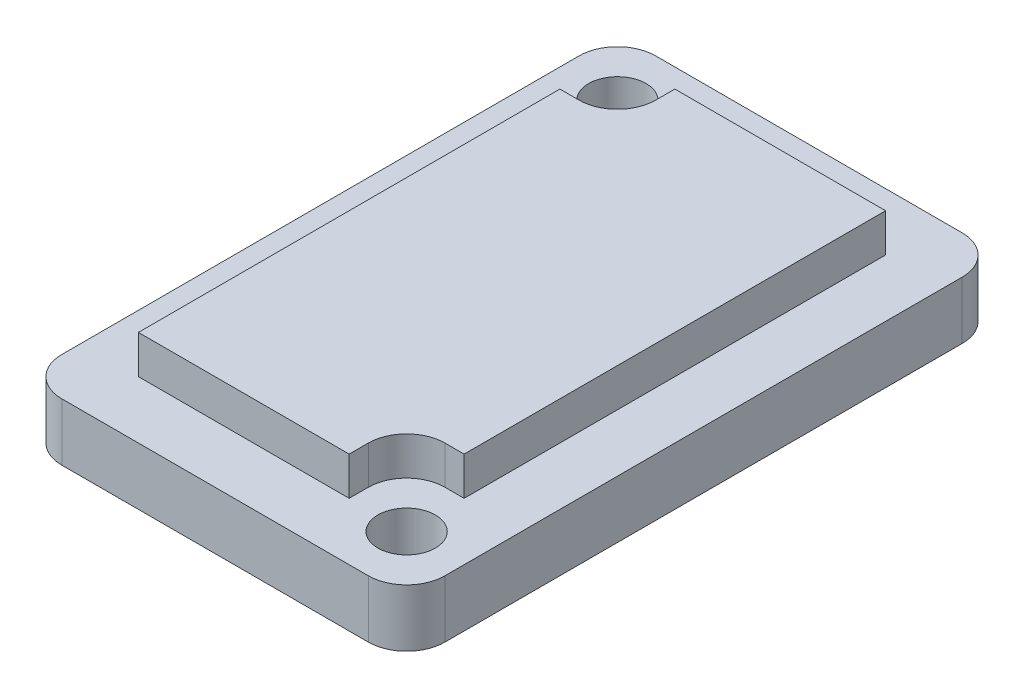
SolidWorks part; units mm, degrees
ref_plane "Alzado" through (0, 0, 0) normal (0, 0, 1) x (1, 0, 0)
ref_plane "Planta" through (0, 0, 0) normal (0, 1, 0) x (1, 0, 0)
ref_plane "Vista lateral" through (0, 0, 0) normal (1, 0, 0) x (0, 0, -1)
sketch "Croquis1" plane through (0, 0, 0) normal (0, 1, 0) x (1, 0, 0)
  line L7 (-10, -15.5) -> (10, -15.5)
  line L8 (-10, -15.5) -> (-10, 15.5)
  line L9 (-10, 15.5) -> (10, 15.5)
  line L10 (10, -15.5) -> (10, 15.5)
  point P0 (0, 0)
  point P3 (3.988, 15.5)
  point P6 (0, 0)
  dimension "D1" = 20
  dimension "D2" = 31
  dimension "D3" = 10
  dimension "D4" = 15.5
extrude "Saliente-Extruir1" add sketch "Croquis1" along normal blind 3
fillet "Redondeo1" radius 2 4 edges at (-10, 1.5, -15.5) (-10, 1.5, 15.5) (10, 1.5, -15.5) (10, 1.5, 15.5)
sketch "Croquis2" plane through (0, 3, 0) normal (0, 1, 0) x (1, 0, 0)
  line L0 (10, -13.5) -> (10, 13.5) construction
  line L1 (-7, -12.5) -> (4, -12.5)
  line L2 (-7, -12.5) -> (-7, 9.5)
  line L3 (-4, 12.5) -> (7, 12.5)
  line L4 (7, -9.5) -> (7, 12.5)
  line L5 (-7, -12.5) -> (7, 12.5) construction
  line L6 (-5.32, 9.5) -> (5.32, -9.5) construction
  line L7 (8, 15.5) -> (-8, 15.5) construction
  line L8 (-7, 9.5) -> (-6, 9.5)
  line L9 (-4, 11.5) -> (-4, 12.5)
  line L10 (4, -12.5) -> (4, -11.5)
  line L11 (6, -9.5) -> (7, -9.5)
  arc A0 (6, -9.5) -> (4, -11.5) centre (6, -11.5) ccw
  arc A1 (-6, 9.5) -> (-4, 11.5) centre (-6, 11.5) ccw
  point P0 (0, 0)
  point P20 (-4, 9.5)
  dimension "D8" = 2
  dimension "D1" = 3
  dimension "D2" = 3
  dimension "D3" = 3
  dimension "D4" = 3
  dimension "D5" = 3
  dimension "D6" = 3
  dimension "D7" = 11
extrude "Saliente-Extruir2" add sketch "Croquis2" along normal blind 2
sketch "Croquis3" plane through (0, 3, 0) normal (0, 1, 0) x (1, 0, 0)
  line L0 (-10, 13.5) -> (-10, -13.5) construction
  line L1 (8, 15.5) -> (-8, 15.5) construction
  line L2 (-8, -15.5) -> (8, -15.5) construction
  line L5 (10, -13.5) -> (10, 13.5) construction
  circle A0 centre (-7, 12.5) radius 1.5
  circle A1 centre (7, -12.5) radius 1.5
  point P12 (7, -8.7669)
  dimension "D1" = 3
  dimension "D4" = 3
  dimension "D2" = 3
  dimension "D3" = 3
  dimension "D5" = 3
  dimension "D6" = 3
extrude "Cortar-Extruir1" cut sketch "Croquis3" against normal blind 4
